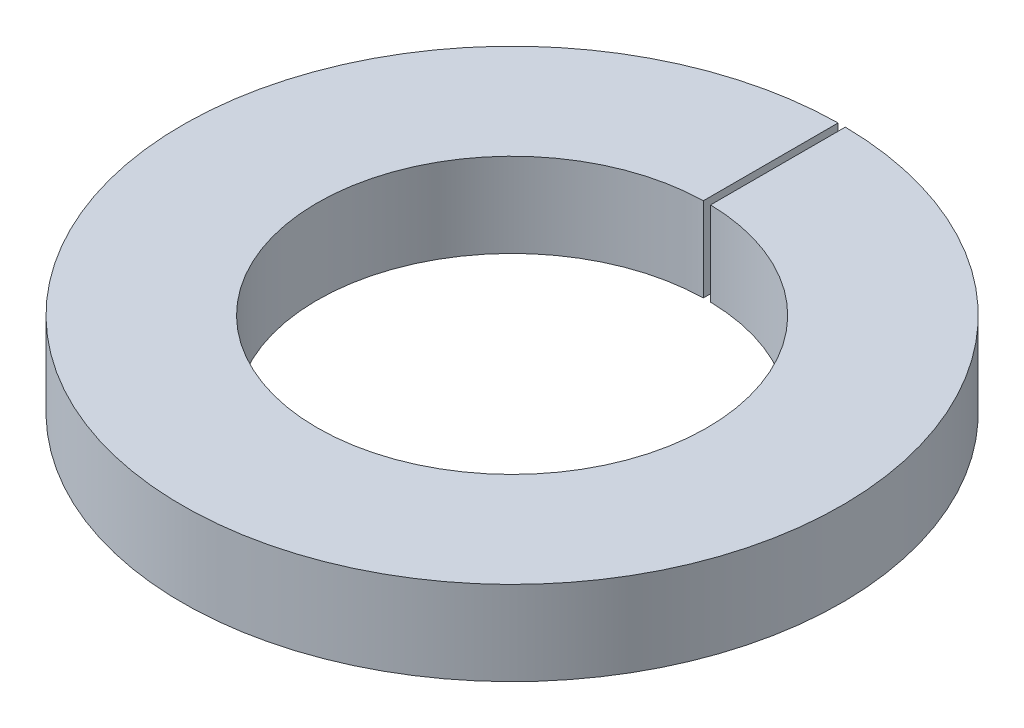
SolidWorks part; units mm, degrees
material "12Х18Н10Т ГОСТ 4543-71"
ref_plane "Спереди" through (0, 0, 0) normal (0, 0, 1) x (1, 0, 0)
ref_plane "Сверху" through (0, 0, 0) normal (0, 1, 0) x (1, 0, 0)
ref_plane "Справа" through (0, 0, 0) normal (1, 0, 0) x (0, 0, -1)
sketch "Эскиз1" plane through (0, 0, 0) normal (0, 1, 0) x (1, 0, 0)
  circle A0 centre (0, 0) radius 8.1
  circle A1 centre (0, 0) radius 13.7
  dimension "D1" = 16.2
  dimension "D2" = 27.4
extrude "Бобышка-Вытянуть1" add sketch "Эскиз1" along normal blind 3.5
sketch "Эскиз2" plane through (0, 3.5, 0) normal (0, 1, 0) x (1, 0, 0)
  line L0 (0.15, 0) -> (-0.15, 0)
  line L1 (-0.15, 0) -> (-0.15, 40)
  line L2 (-0.15, 40) -> (0.15, 40)
  line L3 (0.15, 40) -> (0.15, 0)
  point P4 (0, 0)
  dimension "D1" = 0.3
  dimension "D2" = 40
extrude "Вырез-Вытянуть1" cut sketch "Эскиз2" against normal through all
